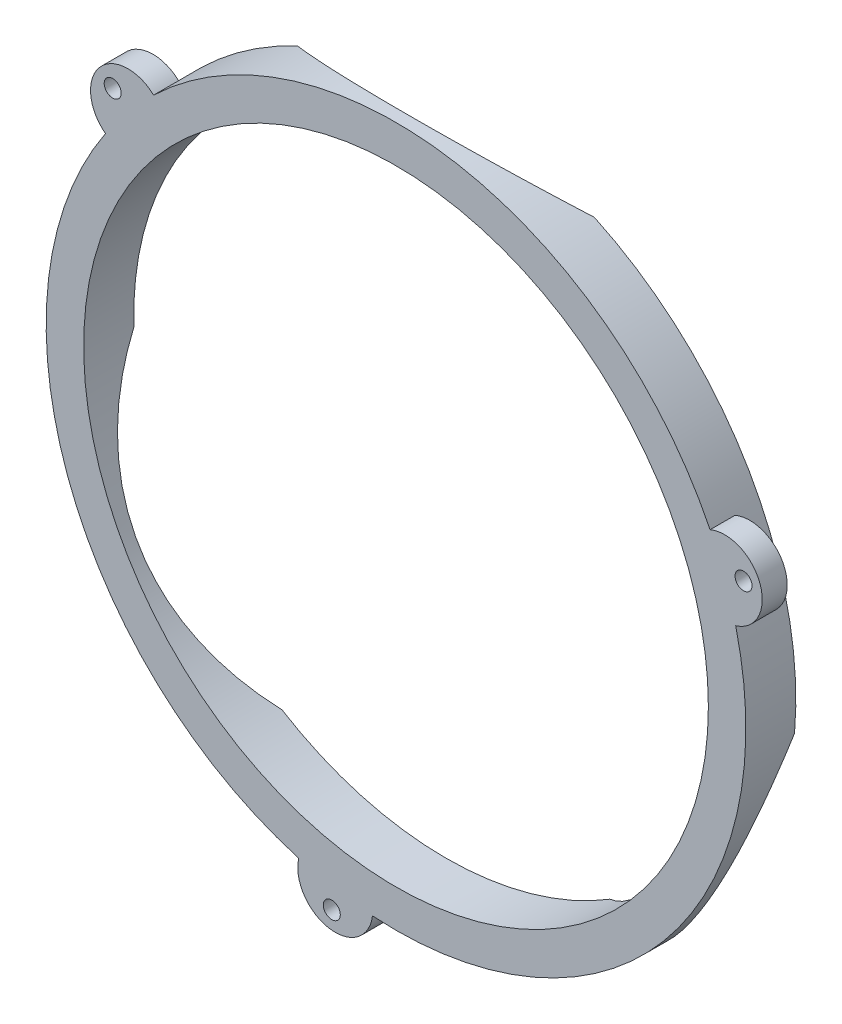
SolidWorks part; units mm, degrees
ref_plane "Piano frontale" through (0, 0, 0) normal (0, 0, 1) x (1, 0, 0)
ref_plane "Piano superiore" through (0, 0, 0) normal (0, 1, 0) x (1, 0, 0)
ref_plane "Piano destro" through (0, 0, 0) normal (1, 0, 0) x (0, 0, -1)
sketch "Schizzo1" plane through (0, 0, 0) normal (0, 0, 1) x (1, 0, 0)
  circle A0 centre (0, 0) radius 62.5
  circle A1 centre (0, 0) radius 70
  dimension "D1" = 125
  dimension "D2" = 140
extrude "Estrusione-Estrusione1" add sketch "Schizzo1" along normal blind 10
sketch "Schizzo5" plane through (0, 0, 0) normal (0, 0, -1) x (-1, 0, 0)
  line L0 (0, 0) -> (12.1554, -68.9365) construction
  line L1 (0, 0) -> (0, -9.0687) construction
  circle A3 centre (0, 0) radius 70 construction
  arc A4 (4.7102, -69.8414) -> (19.4611, -67.2404) centre (12.1554, -68.9365) ccw
  arc A5 (4.7102, -69.8414) -> (19.4611, -67.2404) centre (0, 0) ccw
  dimension "D1" = 15
  dimension "D2" = 10
extrude "Estrusione-Estrusione3" add sketch "Schizzo5" along normal blind 5 from surface at -10 starting at face at (70, 0, 10)
sketch "Schizzo9" plane through (0, 0, 5) normal (0, 0, -1) x (-1, 0, 0)
  line L0 (0, 0) -> (13.4577, -76.3226) construction
  arc A1 (4.7102, -69.8414) -> (19.4611, -67.2404) centre (12.1554, -68.9365) ccw construction
  point P6 (12.85, -72.8758)
  dimension "D1" = 74
hole_wizard "Foro per Vite M3-2" positions "Schizzo12" profile "Schizzo13" hole size "M3" standard "ISO" end condition up to next
sketch "Schizzo12" plane through (0, 0, 5) normal (0, 0, -1) x (-1, 0, 0)
  point P0 (12.85, -72.8758)
sketch "Schizzo13" plane through (-12.85, -72.8758, 5) normal (1, 0, 0) x (0, 1, 0)
  line L0 (0, 0) -> (0, 5)
  line L1 (0, 5) -> (1.7, 5)
  line L2 (1.7, 5) -> (1.7, 0)
  line L5 (1.7, 0) -> (0, 0)
  line L11 (0, -6.35) -> (0, 107.95) construction
  dimension "Thru Hole Dia." = 3.4
  dimension "Thru Hole Depth" = 5
pattern_circular "RipetizioneCircolare3" count 3 over 360 about axis through (0, 0, 0) along (0, 0, 1) of "Estrusione-Estrusione3", "Foro per Vite M3-2"
ref_plane "Piano1" through (-60.6218, -35, 0) normal (-0.866, -0.5, 0) x (0, 0, -1)
sketch "Schizzo14" plane through (-60.6218, -35, 0) normal (-0.866, -0.5, 0) x (0, 0, -1)
  line L0 (-10, 48.5013) -> (-10, -62.8395) construction
  circle A0 centre (55, 0) radius 62.5
  dimension "D1" = 125
  dimension "D2" = 65
extrude "Taglio-Estrusione1" cut sketch "Schizzo14" against normal blind 30
pattern_circular "RipetizioneCircolare4" count 3 over 360 about axis through (0, 0, 10) along (0, 0, -1) of "Taglio-Estrusione1"
